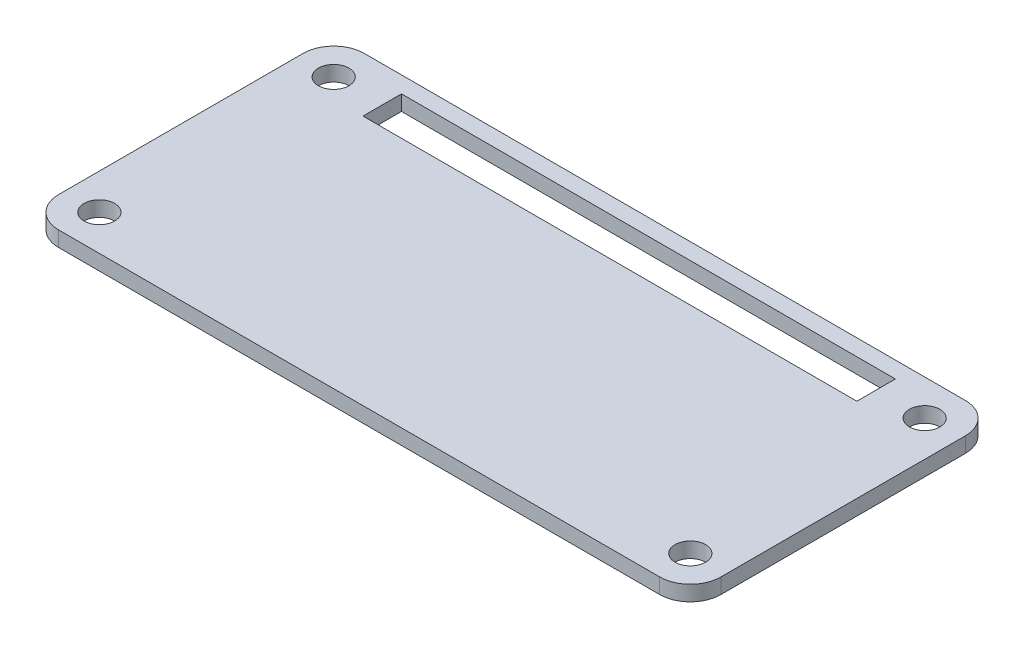
SolidWorks part; units mm, degrees
material "ABS PC"
ref_plane "Front Plane" through (0, 0, 0) normal (0, 0, 1) x (1, 0, 0)
ref_plane "Top Plane" through (0, 0, 0) normal (0, 1, 0) x (1, 0, 0)
ref_plane "Right Plane" through (0, 0, 0) normal (1, 0, 0) x (0, 0, -1)
sketch "Sketch1" plane through (0, 0, 0) normal (0, 1, 0) x (1, 0, 0)
  line L1 (29.5, -15) -> (-29.5, -15)
  line L2 (32.5, -12) -> (32.5, 12)
  line L3 (29.5, 15) -> (-29.5, 15)
  line L4 (-32.5, -12) -> (-32.5, 12)
  line L5 (32.5, -15) -> (-32.5, 15) construction
  line L6 (32.5, 15) -> (-32.5, -15) construction
  line L7 (29, -11.5) -> (-29, -11.5) construction
  line L8 (29, -11.5) -> (29, 11.5) construction
  line L9 (29, 11.5) -> (-29, 11.5) construction
  line L10 (-29, -11.5) -> (-29, 11.5) construction
  line L11 (29, -11.5) -> (-29, 11.5) construction
  line L12 (29, 11.5) -> (-29, -11.5) construction
  line L13 (24.2351, 13.3895) -> (-24.2351, 13.3895)
  line L14 (24.2351, 13.3895) -> (24.2351, 9.6105)
  line L15 (24.2351, 9.6105) -> (-24.2351, 9.6105)
  line L16 (-24.2351, 13.3895) -> (-24.2351, 9.6105)
  line L17 (24.2351, 13.3895) -> (-24.2351, 9.6105) construction
  line L18 (24.2351, 9.6105) -> (-24.2351, 13.3895) construction
  arc A0 (29.5, -15) -> (32.5, -12) centre (29.5, -12) ccw
  arc A1 (32.5, 12) -> (29.5, 15) centre (29.5, 12) ccw
  arc A2 (-29.5, -15) -> (-32.5, -12) centre (-29.5, -12) cw
  arc A3 (-29.5, 15) -> (-32.5, 12) centre (-29.5, 12) ccw
  circle A4 centre (-29, 11.5) radius 1.5
  circle A5 centre (29, 11.5) radius 1.5
  circle A6 centre (29, -11.5) radius 1.5
  circle A7 centre (-29, -11.5) radius 1.5
  point P0 (0, 0)
  point P18 (0, 0)
  point P27 (0, 11.5)
  dimension "D3" = 3
  dimension "D4" = 3
  dimension "D1" = 30
  dimension "D2" = 65
  dimension "D5" = 58
  dimension "D6" = 23
extrude "Boss-Extrude1" add sketch "Sketch1" along normal blind 1.5
